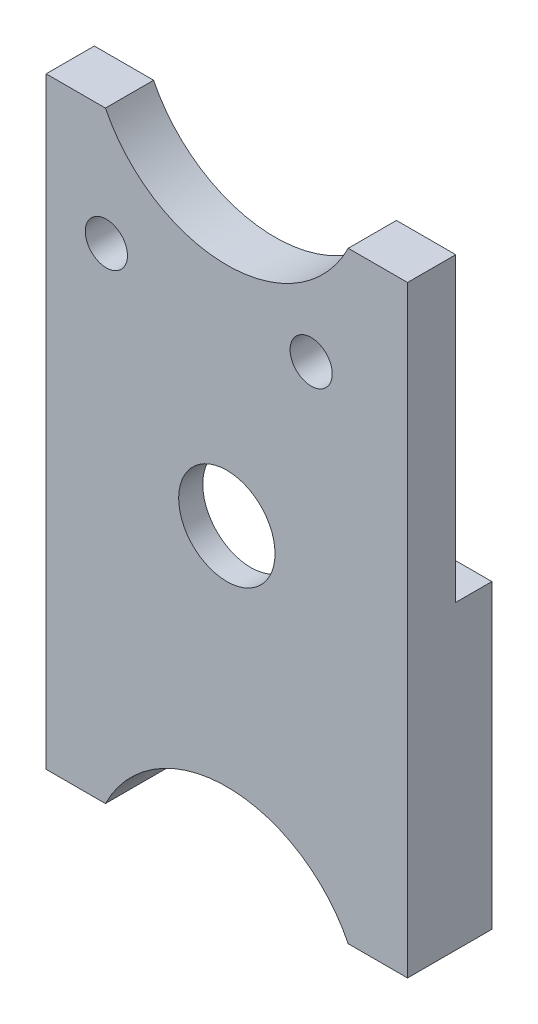
SolidWorks part; units mm, degrees
ref_plane "Спереди" through (0, 0, 0) normal (0, 0, 1) x (1, 0, 0)
ref_plane "Сверху" through (0, 0, 0) normal (0, 1, 0) x (1, 0, 0)
ref_plane "Справа" through (0, 0, 0) normal (1, 0, 0) x (0, 0, -1)
sketch "Эскиз1" plane through (0, 0, 0) normal (0, 0, 1) x (1, 0, 0)
  line L0 (0, 0) -> (0, -30) construction
  line L1 (-15, -25) -> (-10.0778, -25)
  line L2 (-15, -25) -> (-15, 25)
  line L3 (-15, 25) -> (-10.0778, 25)
  line L4 (15, -25) -> (15, 25)
  line L5 (-15, -25) -> (15, 25) construction
  line L6 (-15, 25) -> (15, -25) construction
  line L7 (10.0778, -25) -> (15, -25)
  line L8 (0, 0) -> (0, 18.75) construction
  line L9 (10.0778, 25) -> (15, 25)
  line L10 (-10.0778, 25) -> (10.0778, 25) construction
  line L11 (0, 18.75) -> (0, 25) construction
  circle A0 centre (0, 0) radius 4
  arc A1 (10.0778, -25) -> (-10.0778, -25) centre (0, -30) ccw
  arc A2 (-10.0778, 25) -> (10.0778, 25) centre (0, 30) ccw
  point P0 (0, 0)
  dimension "D3" = 8
  dimension "D5" = 22.5
  dimension "D7" = 22.5
  dimension "D1" = 30
  dimension "D2" = 50
  dimension "D4" = 30
  dimension "D6" = 30
extrude "Бобышка-Вытянуть1" add sketch "Эскиз1" along normal blind 7
sketch "Эскиз3" plane through (0, 0, 7) normal (0, 0, 1) x (1, 0, 0)
  line L0 (15, 0) -> (-15, 0) construction
  line L1 (15, -25) -> (15, 25) construction
  line L2 (-15, 25) -> (-15, -25) construction
  line L3 (-15, 15.3) -> (15, 15.3) construction
  circle A0 centre (-10, 15.3) radius 1.75
  circle A1 centre (7, 15.3) radius 1.75
  dimension "D2" = 3.5
  dimension "D3" = 3.5
  dimension "D4" = 5
  dimension "D1" = 15.3
  dimension "D5" = 22
extrude "Вырез-Вытянуть2" cut sketch "Эскиз3" against normal blind 10
sketch "Эскиз4" plane through (0, 0, 0) normal (0, 0, -1) x (-1, 0, 0)
  line L0 (-15, 0) -> (-4, 0)
  line L1 (-15, -25) -> (-15, 25) construction
  line L2 (15, 25) -> (15, -25) construction
  line L7 (15, 25) -> (15, 0)
  line L9 (4, 0) -> (15, 0)
  line L10 (-15, 0) -> (-15, 25)
  line L11 (-15, 25) -> (15, 25)
  arc A0 (4, 0) -> (-4, 0) centre (0, 0) ccw
  dimension "D1" = 4
extrude "Вырез-Вытянуть4" cut sketch "Эскиз4" against normal blind 3
sketch "Эскиз6" plane through (0, 0, 0) normal (0, 0, -1) x (-1, 0, 0)
  circle A0 centre (0, 0) radius 11.25
  dimension "D1" = 22.5
extrude "Вырез-Вытянуть5" cut sketch "Эскиз6" against normal blind 5
